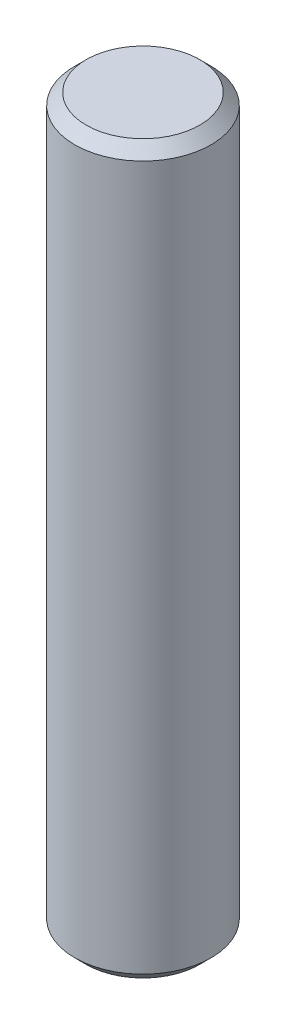
SolidWorks part; units mm, degrees
material "Plain Carbon Steel"
ref_plane "Front Plane" through (0, 0, 0) normal (0, 0, 1) x (1, 0, 0)
ref_plane "Top Plane" through (0, 0, 0) normal (0, 1, 0) x (1, 0, 0)
ref_plane "Right Plane" through (0, 0, 0) normal (1, 0, 0) x (0, 0, -1)
sketch "Sketch1" plane through (0, 0, 0) normal (0, 1, 0) x (1, 0, 0)
  circle A0 centre (0, 0) radius 3
  dimension "D1" = 6
extrude "Boss-Extrude1" add sketch "Sketch1" against normal blind 32
chamfer "Chamfer1" distance 0.5 angle 45 2 edges at (0, -32, 3) (0, 0, 3)
cosmetic thread "Cosmetic Thread1" parameters "D2"=4.891
